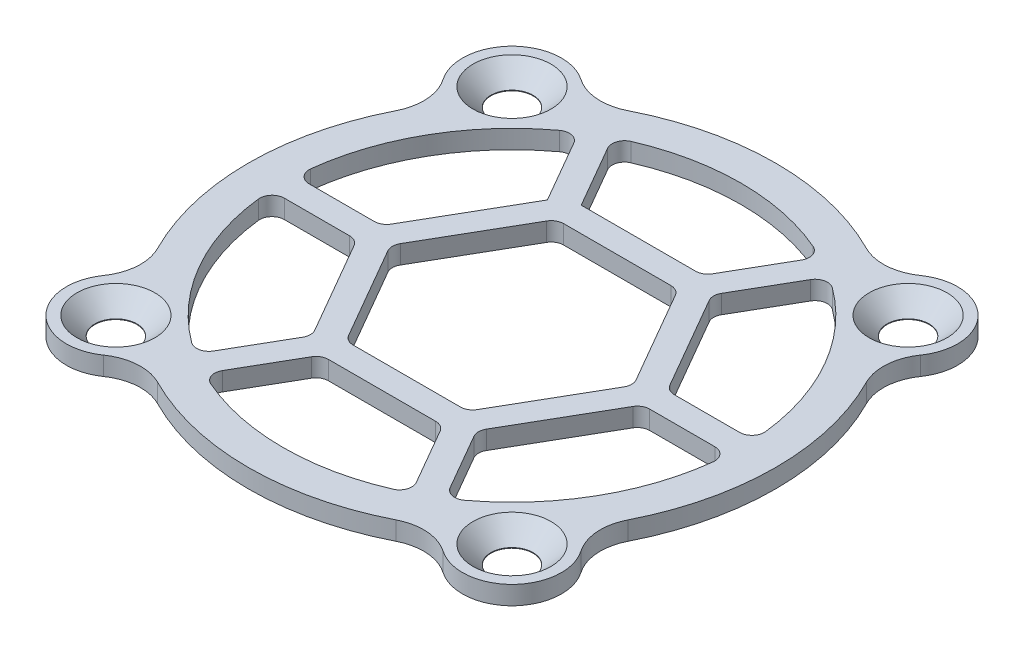
SolidWorks part; units mm, degrees
ref_plane "Plan de face" through (0, 0, 0) normal (0, 0, 1) x (1, 0, 0)
ref_plane "Plan de dessus" through (0, 0, 0) normal (0, 1, 0) x (1, 0, 0)
ref_plane "Plan de droite" through (0, 0, 0) normal (1, 0, 0) x (0, 0, -1)
sketch "Esquisse1" plane through (0, 0, 0) normal (0, 1, 0) x (1, 0, 0)
  line L0 (-16, 16) -> (16, -16) construction
  line L1 (-16, 16) -> (16, 16) construction
  line L2 (-16, 16) -> (-16, -16) construction
  line L3 (-16, -16) -> (16, -16) construction
  line L4 (16, 16) -> (16, -16) construction
  line L5 (-16, 16) -> (16, -16) construction
  line L6 (-16, -16) -> (16, 16) construction
  line L7 (-13.1716, 18.8284) -> (18.8284, -13.1716)
  line L8 (-18.8284, 13.1716) -> (13.1716, -18.8284)
  line L9 (-16, -16) -> (16, 16) construction
  line L10 (-18.8284, -13.1716) -> (13.1716, 18.8284)
  line L11 (-13.1716, -18.8284) -> (18.8284, 13.1716)
  circle A0 centre (0, 0) radius 19.5 construction
  circle A1 centre (-16, 16) radius 1.5 construction
  circle A2 centre (16, 16) radius 1.5 construction
  circle A3 centre (16, -16) radius 1.5 construction
  circle A4 centre (-16, -16) radius 1.5 construction
  arc A5 (-13.1716, 18.8284) -> (-18.8284, 13.1716) centre (-16, 16) ccw
  arc A6 (13.1716, -18.8284) -> (18.8284, -13.1716) centre (16, -16) ccw
  arc A7 (-18.8284, -13.1716) -> (-13.1716, -18.8284) centre (-16, -16) ccw
  arc A8 (18.8284, 13.1716) -> (13.1716, 18.8284) centre (16, 16) ccw
  circle A9 centre (0, 0) radius 18.5
  circle A10 centre (0, 0) radius 21.3
  point P0 (0, 0)
  point P12 (0, 0)
  point P17 (0, 0)
  dimension "D2" = 39
  dimension "D3" = 3
  dimension "D4" = 4
  dimension "D1" = 32
  dimension "D5" = 1
  dimension "D6" = 1.8
extrude "Boss.-Extru.1" add sketch "Esquisse1" along normal blind 1.5 contours A10 L7 A5 L8 | L8 A10 L10 A9 | L7 A10 L8 A9 | L10 A10 L7 A9 | A10 L11 A8 L10 | L11 A10 L10 A9 | L7 A10 L11 A9 | A10 L10 A7 L11 | L10 A10 L11 A9 | L11 A10 L8 A9 | L8 A10 L7 A9 | A10 L8 A6 L7
hole_wizard "Fraisage pour vis à tête fraisée M31" positions "Esquisse2" profile "Esquisse3" countersink size "M3" standard "Ansi Metric" end condition through all
sketch "Esquisse2" plane through (0, 1.5, 0) normal (0, 1, 0) x (1, 0, 0)
  point P0 (-16, 16)
  point P3 (16, 16)
  point P6 (16, -16)
  point P9 (-16, -16)
sketch "Esquisse3" plane through (-16, 1.5, -16) normal (1, 0, 0) x (0, 0, 1)
  line L0 (0, 0) -> (0, 1.5)
  line L1 (0, 1.5) -> (1.7, 1.5)
  line L2 (1.7, 1.5) -> (1.7, 1.45)
  line L3 (1.7, 1.45) -> (3.15, 0)
  line L5 (3.15, 0) -> (0, 0)
  line L6 (-1.7, 1.45) -> (-3.15, 0) construction
  line L11 (0, -6.35) -> (0, 107.95) construction
  dimension "Diamètre du perçage jusqu'au prochain" = 3.4
  dimension "Profondeur du perçage jusqu'au prochain" = 1.5
  dimension "Diamètre du fraisage entrant" = 6.3
  dimension "Angle du fraisage entrant" = 90
sketch "Esquisse4" plane through (0, 0, 0) normal (0, 1, 0) x (1, 0, 0)
  line L0 (-6.0622, 10.5) -> (-12.1244, 0)
  line L1 (4.9075, -8.5) -> (9.815, 0)
  line L2 (9.815, 0) -> (4.9075, 8.5)
  line L3 (4.9075, 8.5) -> (-4.9075, 8.5)
  line L4 (-4.9075, 8.5) -> (-9.815, 0)
  line L5 (-9.815, 0) -> (-4.9075, -8.5)
  line L6 (-4.9075, -8.5) -> (4.9075, -8.5)
  line L7 (-12.1244, 0) -> (-6.0622, -10.5)
  line L8 (-6.0622, -10.5) -> (6.0622, -10.5)
  line L9 (6.0622, -10.5) -> (12.1244, 0)
  line L10 (12.1244, 0) -> (6.0622, 10.5)
  line L11 (6.0622, 10.5) -> (-6.0622, 10.5)
  line L12 (-6.0622, -8.5) -> (-12.1244, -19)
  line L13 (4.9075, -27.5) -> (9.815, -19)
  line L14 (9.815, -19) -> (4.9075, -10.5)
  line L15 (4.9075, -10.5) -> (-4.9075, -10.5)
  line L16 (-4.9075, -10.5) -> (-9.815, -19)
  line L17 (-9.815, -19) -> (-4.9075, -27.5)
  line L18 (-4.9075, -27.5) -> (4.9075, -27.5)
  line L19 (-12.1244, -19) -> (-6.0622, -29.5)
  line L20 (-6.0622, -29.5) -> (6.0622, -29.5)
  line L21 (6.0622, -29.5) -> (12.1244, -19)
  line L22 (12.1244, -19) -> (6.0622, -8.5)
  line L23 (6.0622, -8.5) -> (-6.0622, -8.5)
  line L24 (-11.547, -18) -> (-6.6395, -9.5)
  line L25 (-6.6395, -9.5) -> (-11.547, -1)
  line L26 (-11.547, -1) -> (-21.362, -1)
  line L27 (-21.362, -1) -> (-26.2694, -9.5)
  line L28 (-26.2694, -9.5) -> (-21.362, -18)
  line L29 (-21.362, -18) -> (-11.547, -18)
  line L30 (-10.3923, -20) -> (-4.3301, -9.5)
  line L31 (-4.3301, -9.5) -> (-10.3923, 1)
  line L32 (-10.3923, 1) -> (-22.5167, 1)
  line L33 (-22.5167, 1) -> (-28.5788, -9.5)
  line L34 (-28.5788, -9.5) -> (-22.5167, -20)
  line L35 (-22.5167, -20) -> (-10.3923, -20)
  line L36 (-21.362, 1) -> (-11.547, 1)
  line L37 (-11.547, 1) -> (-6.6395, 9.5)
  line L38 (-6.6395, 9.5) -> (-11.547, 18)
  line L39 (-11.547, 18) -> (-21.362, 18)
  line L40 (-21.362, 18) -> (-26.2694, 9.5)
  line L41 (-26.2694, 9.5) -> (-21.362, 1)
  line L42 (-22.5167, -1) -> (-10.3923, -1)
  line L43 (-10.3923, -1) -> (-4.3301, 9.5)
  line L44 (-4.3301, 9.5) -> (-10.3923, 20)
  line L45 (-10.3923, 20) -> (-22.5167, 20)
  line L46 (-22.5167, 20) -> (-28.5788, 9.5)
  line L47 (-28.5788, 9.5) -> (-22.5167, -1)
  line L48 (-9.815, 19) -> (-4.9075, 10.5)
  line L49 (-4.9075, 10.5) -> (4.9075, 10.5)
  line L50 (4.9075, 10.5) -> (9.815, 19)
  line L51 (9.815, 19) -> (4.9075, 27.5)
  line L52 (4.9075, 27.5) -> (-4.9075, 27.5)
  line L53 (-4.9075, 27.5) -> (-9.815, 19)
  line L54 (-12.1244, 19) -> (-6.0622, 8.5)
  line L55 (-6.0622, 8.5) -> (6.0622, 8.5)
  line L56 (6.0622, 8.5) -> (12.1244, 19)
  line L57 (12.1244, 19) -> (6.0622, 29.5)
  line L58 (6.0622, 29.5) -> (-6.0622, 29.5)
  line L59 (-6.0622, 29.5) -> (-12.1244, 19)
  line L60 (11.547, 18) -> (6.6395, 9.5)
  line L61 (6.6395, 9.5) -> (11.547, 1)
  line L62 (11.547, 1) -> (21.362, 1)
  line L63 (21.362, 1) -> (26.2694, 9.5)
  line L64 (26.2694, 9.5) -> (21.362, 18)
  line L65 (21.362, 18) -> (11.547, 18)
  line L66 (10.3923, 20) -> (4.3301, 9.5)
  line L67 (4.3301, 9.5) -> (10.3923, -1)
  line L68 (10.3923, -1) -> (22.5167, -1)
  line L69 (22.5167, -1) -> (28.5788, 9.5)
  line L70 (28.5788, 9.5) -> (22.5167, 20)
  line L71 (22.5167, 20) -> (10.3923, 20)
  line L72 (21.362, -1) -> (11.547, -1)
  line L73 (11.547, -1) -> (6.6395, -9.5)
  line L74 (6.6395, -9.5) -> (11.547, -18)
  line L75 (11.547, -18) -> (21.362, -18)
  line L76 (21.362, -18) -> (26.2694, -9.5)
  line L77 (26.2694, -9.5) -> (21.362, -1)
  line L78 (22.5167, 1) -> (10.3923, 1)
  line L79 (10.3923, 1) -> (4.3301, -9.5)
  line L80 (4.3301, -9.5) -> (10.3923, -20)
  line L81 (10.3923, -20) -> (22.5167, -20)
  line L82 (22.5167, -20) -> (28.5788, -9.5)
  line L83 (28.5788, -9.5) -> (22.5167, 1)
  circle A0 centre (0, 0) radius 8.5 construction
  circle A1 centre (0, -19) radius 8.5 construction
  circle A2 centre (0, 0) radius 18.5 construction
  circle A3 centre (0, 0) radius 18.5
  point P91 (0, 0)
  dimension "D1" = 21
  dimension "D2" = 2
  dimension "D3" = 2
  dimension "D4" = 6
extrude "Boss.-Extru.2" add sketch "Esquisse4" along normal blind 1.5 contours L44 A3 L38 L0 L11 | L54 L55 L43 L44 L11 L0 | L67 L66 L11 L44 L43 L3 | L55 L54 L0 L32 L31 L4 | L32 A3 L26 L7 L0 | L42 L43 L31 L32 L0 L7 | L12 A3 L16 L8 L7 | L43 L42 L7 L12 L23 L5 | L30 L31 L23 L12 L7 L8 | L80 L79 L6 L31 L30 L8 | L79 L80 L8 L9 L22 L23 | L80 A3 L74 L9 L8 | L68 L67 L1 L23 L22 L9 | L79 L78 L10 L56 L55 L2 | L78 L79 L67 L68 L9 L10 | L68 A3 L62 L10 L9 | L66 L67 L55 L56 L10 L11 | L56 A3 L50 L11 L10
fillet "Congé1" radius 4 8 edges at (-17.6218, 0.75, -11.965) (11.965, 0.75, 17.6218) (-11.965, 0.75, 17.6218) (17.6218, 0.75, -11.965) (-17.6218, 0.75, 11.965) (11.965, 0.75, -17.6218) (-11.965, 0.75, -17.6218) (17.6218, 0.75, 11.965)
fillet "Congé2" radius 1 28 edges at (6.6395, 0.75, 9.5) (4.9075, 0.75, 10.5) (6.6395, 0.75, -9.5) (4.9075, 0.75, -8.5) (11.547, 0.75, -1) (9.815, 0.75, 0) (11.547, 0.75, 1) (4.9075, 0.75, 8.5) (4.9075, 0.75, -10.5) (-4.9075, 0.75, -8.5) (-4.9075, 0.75, 8.5) (-4.9075, 0.75, 10.5) (-6.6395, 0.75, 9.5) (-11.547, 0.75, 1) (-11.547, 0.75, -1) (-9.815, 0.75, 0) (-18.473, 0.75, 1) (-18.473, 0.75, -1) (-8.3705, 0.75, 16.498) (-10.1025, 0.75, 15.498) (10.1025, 0.75, 15.498) (8.3705, 0.75, 16.498) (18.473, 0.75, 1) (18.473, 0.75, -1) (10.1025, 0.75, -15.498) (8.3705, 0.75, -16.498) (-8.3705, 0.75, -16.498) (-10.1025, 0.75, -15.498)
